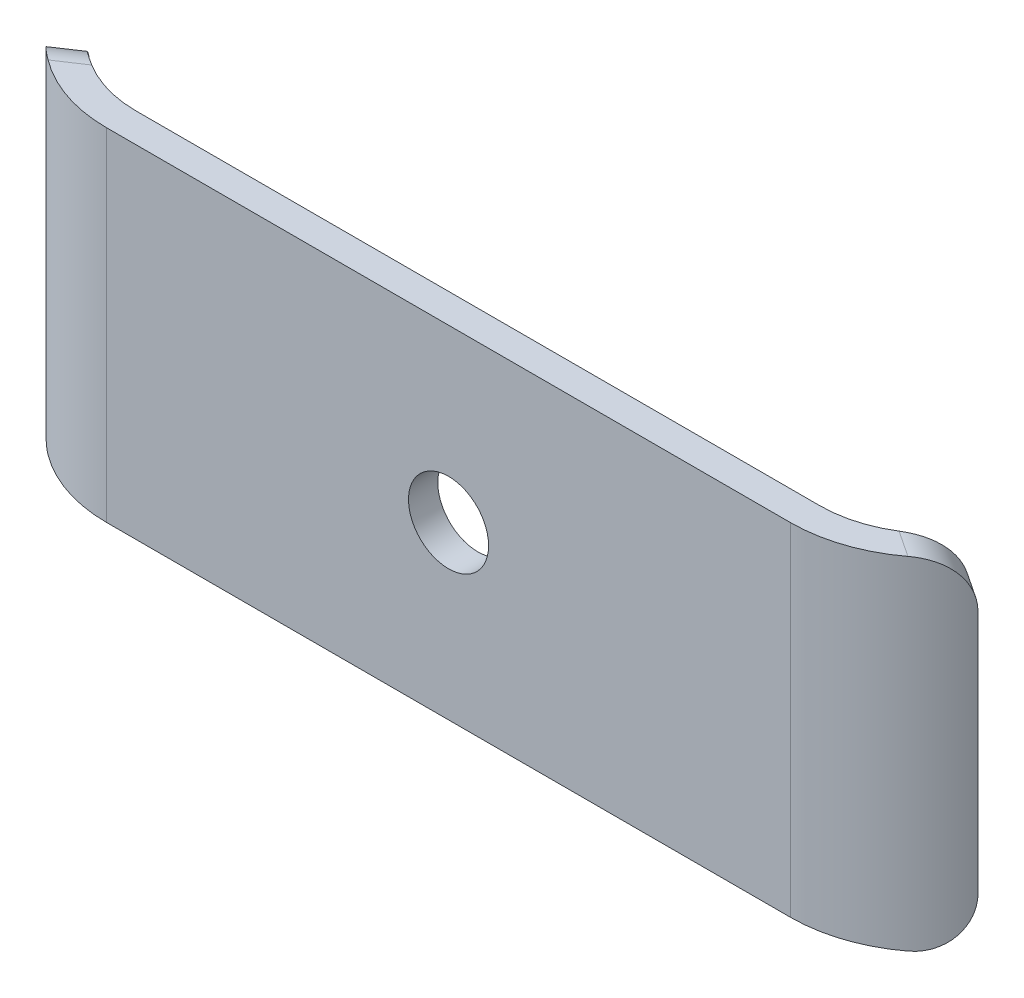
SolidWorks part; units mm, degrees
ref_plane "Front Plane" through (0, 0, 0) normal (0, 0, 1) x (1, 0, 0)
ref_plane "Top Plane" through (0, 0, 0) normal (0, 1, 0) x (1, 0, 0)
ref_plane "Right Plane" through (0, 0, 0) normal (1, 0, 0) x (0, 0, -1)
sketch "Sketch1" plane through (0, 0, 0) normal (0, 1, 0) x (1, 0, 0)
  line L0 (-35, 0) -> (35, 0) construction
  line L1 (-35, 12) -> (35, 12)
  line L2 (-35, -12) -> (35, -12)
  line L4 (-35, -15) -> (35, -15)
  line L5 (-47.5, -8.2916) -> (-45, -6.6332)
  line L6 (45, -6.6332) -> (47.5, -8.2916)
  line L8 (-35, 15) -> (35, 15) construction
  arc A0 (-35, 12) -> (-35, -12) centre (-35, 0) ccw
  arc A1 (35, -12) -> (35, 12) centre (35, 0) ccw
  arc A2 (35, -15) -> (47.5, -8.2916) centre (35, 0) ccw
  arc A3 (-47.5, -8.2916) -> (-35, -15) centre (-35, 0) ccw
  arc A4 (-35, 15) -> (-35, -15) centre (-35, 0) ccw construction
  arc A5 (35, -15) -> (35, 15) centre (35, 0) ccw construction
  point P2 (0, 0)
  dimension "D2" = 12
  dimension "D1" = 70
  dimension "D4" = 10
  dimension "D5" = 10
  dimension "D3" = 3
extrude "Boss-Extrude1" add sketch "Sketch1" along normal blind 35 contours L5 A3 L4 A2 L6 A1 L2 A0
fillet "Fillet1" radius 5 4 edges at (46.25, 0, 7.4624) (46.25, 35, 7.4624) (-46.25, 0, 7.4624) (-46.25, 35, 7.4624)
sketch "Sketch2" plane through (0, 0, 15) normal (0, 0, 1) x (1, 0, 0)
  line L0 (-35, 35) -> (35, 0) construction
  circle A0 centre (0, 17.5) radius 4.1
  dimension "D1" = 8.2
extrude "Cut-Extrude1" cut sketch "Sketch2" against normal up to next
